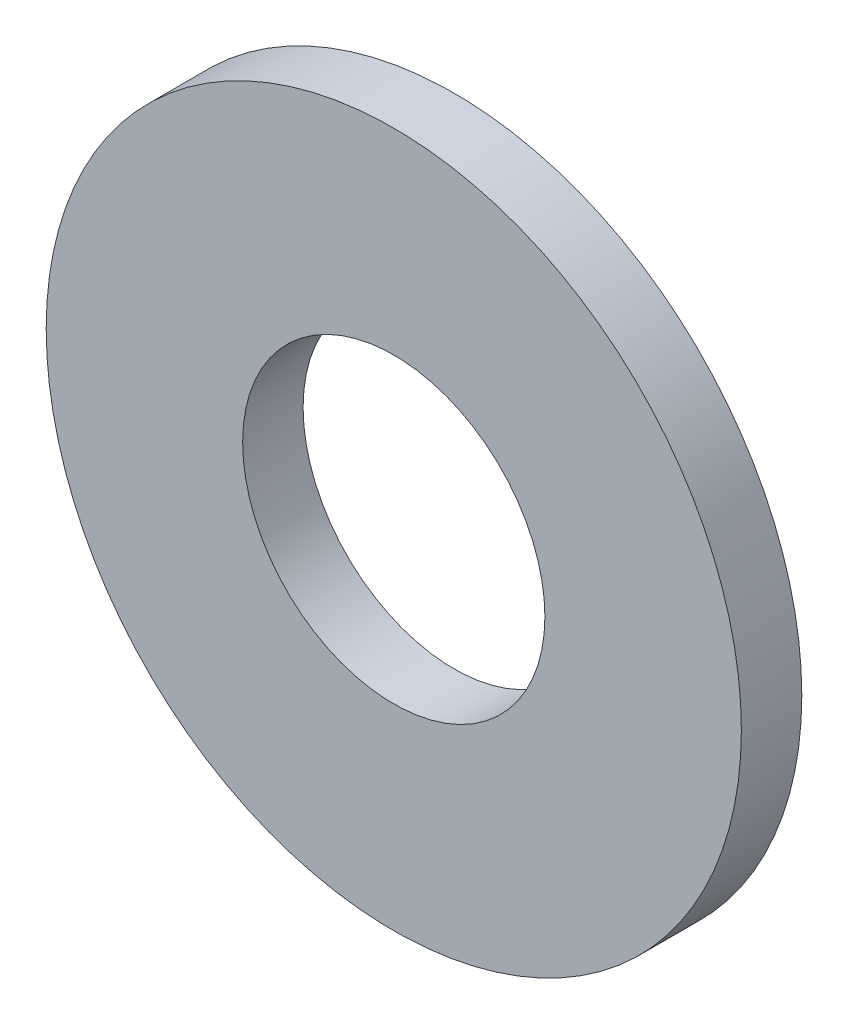
SolidWorks part; units mm, degrees
ref_plane "Plan de face" through (0, 0, 0) normal (0, 0, 1) x (1, 0, 0)
ref_plane "Plan de dessus" through (0, 0, 0) normal (0, 1, 0) x (1, 0, 0)
ref_plane "Plan de droite" through (0, 0, 0) normal (1, 0, 0) x (0, 0, -1)
sketch "Esquisse1" plane through (0, 0, 0) normal (0, 0, 1) x (1, 0, 0)
  circle A0 centre (0, 0) radius 5.75
  circle A1 centre (0, 0) radius 2.5
  dimension "D1" = 11.5
  dimension "D2" = 5
extrude "Boss.-Extru.1" add sketch "Esquisse1" along normal blind 1
